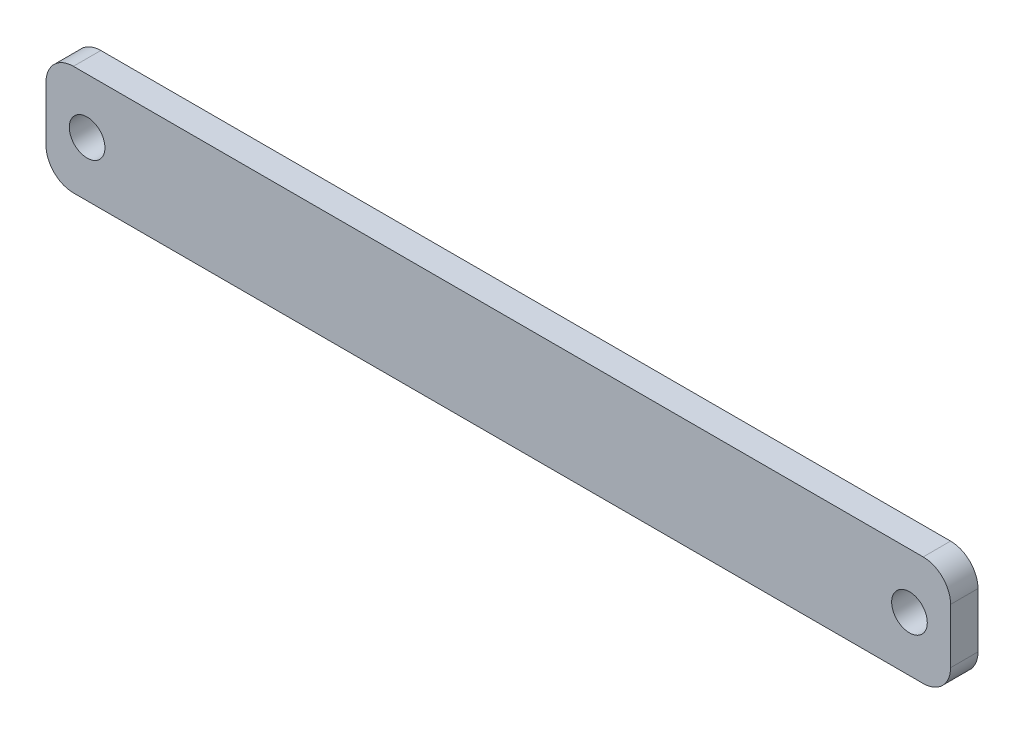
SolidWorks part; units mm, degrees
ref_plane "Front Plane" through (0, 0, 0) normal (0, 0, 1) x (1, 0, 0)
ref_plane "Top Plane" through (0, 0, 0) normal (0, 1, 0) x (1, 0, 0)
ref_plane "Right Plane" through (0, 0, 0) normal (1, 0, 0) x (0, 0, -1)
sketch "Sketch1" plane through (0, 0, 0) normal (0, 0, 1) x (1, 0, 0)
  line L0 (0, 91.9533) -> (0, -82.371) construction
  line L1 (-155, 20) -> (155, 20)
  line L2 (-165, 10) -> (-165, -10)
  line L3 (-155, -20) -> (155, -20)
  line L4 (165, 10) -> (165, -10)
  line L5 (-165, 20) -> (165, -20) construction
  line L6 (-165, -20) -> (165, 20) construction
  line L7 (-150, 0) -> (150, 0) construction
  circle A0 centre (-150, 0) radius 6.5
  circle A1 centre (150, 0) radius 6.5
  arc A2 (155, -20) -> (165, -10) centre (155, -10) ccw
  arc A3 (155, 20) -> (165, 10) centre (155, 10) cw
  arc A4 (-165, -10) -> (-155, -20) centre (-155, -10) ccw
  arc A5 (-155, 20) -> (-165, 10) centre (-155, 10) ccw
  point P0 (0, 0)
  point P27 (0, 0)
  dimension "D3" = 13
  dimension "D5" = 10
  dimension "D1" = 13
  dimension "D2" = 40
  dimension "D4" = 15
  dimension "D6" = 300
extrude "Boss-Extrude1" add sketch "Sketch1" along normal blind 10
